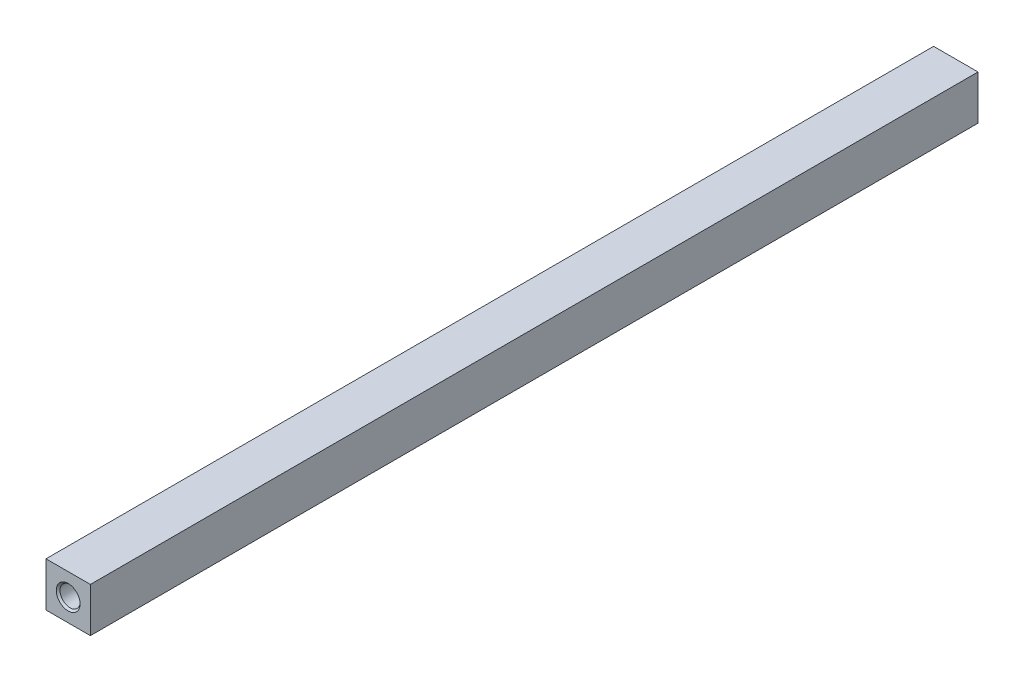
SolidWorks part; units mm, degrees
ref_plane "Ön Düzlem" through (0, 0, 0) normal (0, 0, 1) x (1, 0, 0)
ref_plane "Üst Düzlem" through (0, 0, 0) normal (0, 1, 0) x (1, 0, 0)
ref_plane "Sağ Düzlem" through (0, 0, 0) normal (1, 0, 0) x (0, 0, -1)
sketch "Sketch1" plane through (0, 0, 0) normal (0, 0, 1) x (1, 0, 0)
  line L1 (-7.5, -7.5) -> (7.5, -7.5)
  line L2 (-7.5, -7.5) -> (-7.5, 7.5)
  line L3 (-7.5, 7.5) -> (7.5, 7.5)
  line L4 (7.5, -7.5) -> (7.5, 7.5)
  line L5 (-7.5, -7.5) -> (7.5, 7.5) construction
  line L6 (-7.5, 7.5) -> (7.5, -7.5) construction
  point P0 (0, 0)
  dimension "D1" = 15
extrude "Boss-Extrude1" add sketch "Sketch1" along normal mid plane 300
hole_wizard "M8 Tapped Hole1" positions "Sketch2" profile "Sketch3" tap size "M8" standard "ISO"
sketch "Sketch2" plane through (0, 0, 150) normal (0, 0, 1) x (1, 0, 0)
  point P0 (0, 0)
sketch "Sketch3" plane through (0, 0, 150) normal (1, 0, 0) x (0, -1, 0)
  line L0 (0, 0) -> (0, 24.2929)
  line L1 (0, 24.2929) -> (3.4, 22.25)
  line L2 (3.4, 22.25) -> (3.4, 0.625)
  line L3 (3.4, 0.625) -> (4.025, 0)
  line L5 (4.025, 0) -> (0, 0)
  line L6 (-3.4, 0.625) -> (-4.025, 0) construction
  line L10 (0, 24.2929) -> (-3.4, 22.25) construction
  line L11 (0, -6.35) -> (0, 107.95) construction
  dimension "Tap Drill Dia." = 6.8
  dimension "Tap Drill Depth" = 22.25
  dimension "Near C'Sink Dia." = 8.05
  dimension "Near C'Sink Angle" = 90
  dimension "Drill Angle" = 118
cosmetic thread "Hole Thread1" parameters "D1"=16, "D2"=8
mirror "Mirror1" about plane through (0, 0, 0) normal (0, 0, 1) of "M8 Tapped Hole1"
cosmetic thread "Hole Thread2" parameters "D1"=16, "D2"=8
